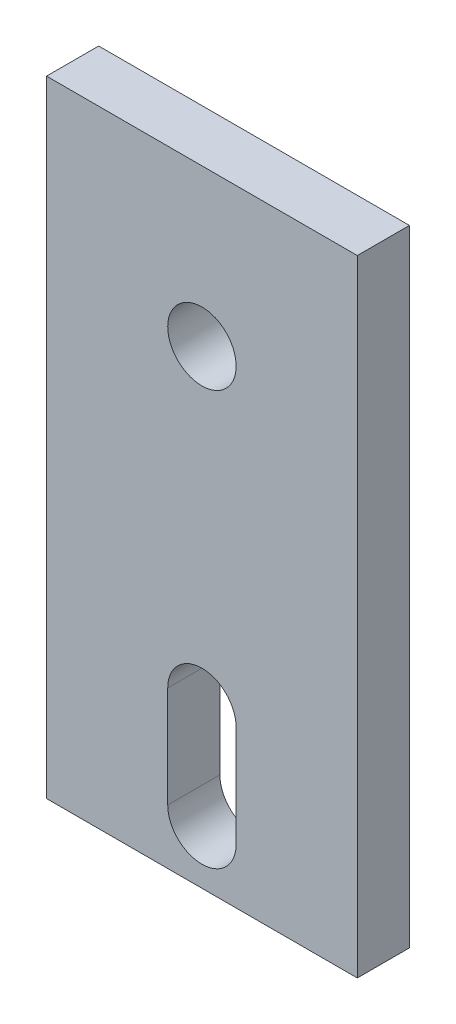
SolidWorks part; units mm, degrees
ref_plane "Front Plane" through (0, 0, 0) normal (0, 0, 1) x (1, 0, 0)
ref_plane "Top Plane" through (0, 0, 0) normal (0, 1, 0) x (1, 0, 0)
ref_plane "Right Plane" through (0, 0, 0) normal (1, 0, 0) x (0, 0, -1)
ref_plane "Plane1" through (0, 0, 6.35) normal (0, 0, 1) x (1, 0, 0)
sketch "Sketch1" plane through (0, 0, 6.35) normal (0, 0, 1) x (1, 0, 0)
  line L0 (18.923, 76.2) -> (-18.923, 76.2)
  line L1 (-18.923, 76.2) -> (-18.923, 0)
  line L2 (-18.923, 0) -> (18.923, 0)
  line L3 (18.923, 0) -> (18.923, 76.2)
  circle A0 centre (0, 57.15) radius 4.1656
  circle A1 centre (0, 19.05) radius 4.1656
extrude "Boss-Extrude1" add sketch "Sketch1" against normal blind 6.35
sketch "Sketch2" plane through (0, 0, 6.35) normal (0, 0, 1) x (1, 0, 0)
  line L0 (0, 6.7056) -> (0, 19.05) construction
  line L1 (-4.1656, 6.7056) -> (-4.1656, 19.05)
  line L2 (4.1656, 6.7056) -> (4.1656, 19.05)
  line L3 (0, 2.54) -> (0, 0) construction
  arc A0 (-4.1656, 6.7056) -> (4.1656, 6.7056) centre (0, 6.7056) ccw
  arc A1 (4.1656, 19.05) -> (-4.1656, 19.05) centre (0, 19.05) ccw
  circle A2 centre (0, 19.05) radius 4.1656 construction
  point P3 (0, 12.8778)
  dimension "D1" = 2.54
extrude "Cut-Extrude1" cut sketch "Sketch2" against normal through all
